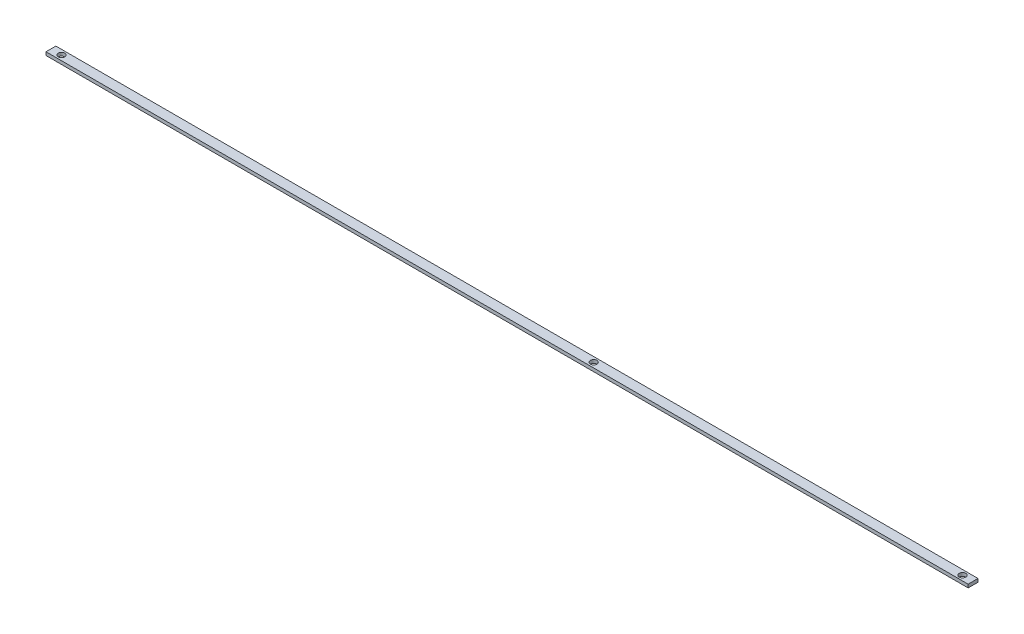
SolidWorks part; units mm, degrees
ref_plane "Front Plane" through (0, 0, 0) normal (0, 0, 1) x (1, 0, 0)
ref_plane "Top Plane" through (0, 0, 0) normal (0, 1, 0) x (1, 0, 0)
ref_plane "Right Plane" through (0, 0, 0) normal (1, 0, 0) x (0, 0, -1)
sketch "Sketch1" plane through (0, 0, 0) normal (0, 1, 0) x (1, 0, 0)
  line L0 (-44.533, 9.525) -> (-44.533, 0)
  line L1 (-44.533, 0) -> (844.467, 0)
  line L2 (844.467, 0) -> (844.467, 9.525)
  line L3 (844.467, 9.525) -> (-44.533, 9.525)
  dimension "D1" = 9.525
  dimension "D2" = 889
extrude "Boss-Extrude1" add sketch "Sketch1" along normal blind 3.175
sketch "Sketch2" plane through (0, 3.175, 0) normal (0, 1, 0) x (1, 0, 0)
  line L0 (-44.533, 0) -> (844.467, 0) construction
  line L1 (-44.533, 9.525) -> (-44.533, 0) construction
  line L2 (844.467, 9.525) -> (-44.533, 9.525) construction
  line L3 (844.467, 0) -> (844.467, 9.525) construction
  circle A0 centre (-34.373, 4.7625) radius 3.175
  circle A1 centre (834.307, 4.7625) radius 3.175
  circle A2 centre (478.707, 4.7625) radius 3.175
  dimension "D1" = 513.08
  dimension "D2" = 4.7625
  dimension "D4" = 4.7625
  dimension "D5" = 10.16
  dimension "D6" = 4.7625
  dimension "D3" = 10.16
extrude "Cut-Extrude1" cut sketch "Sketch2" against normal blind 6.35
